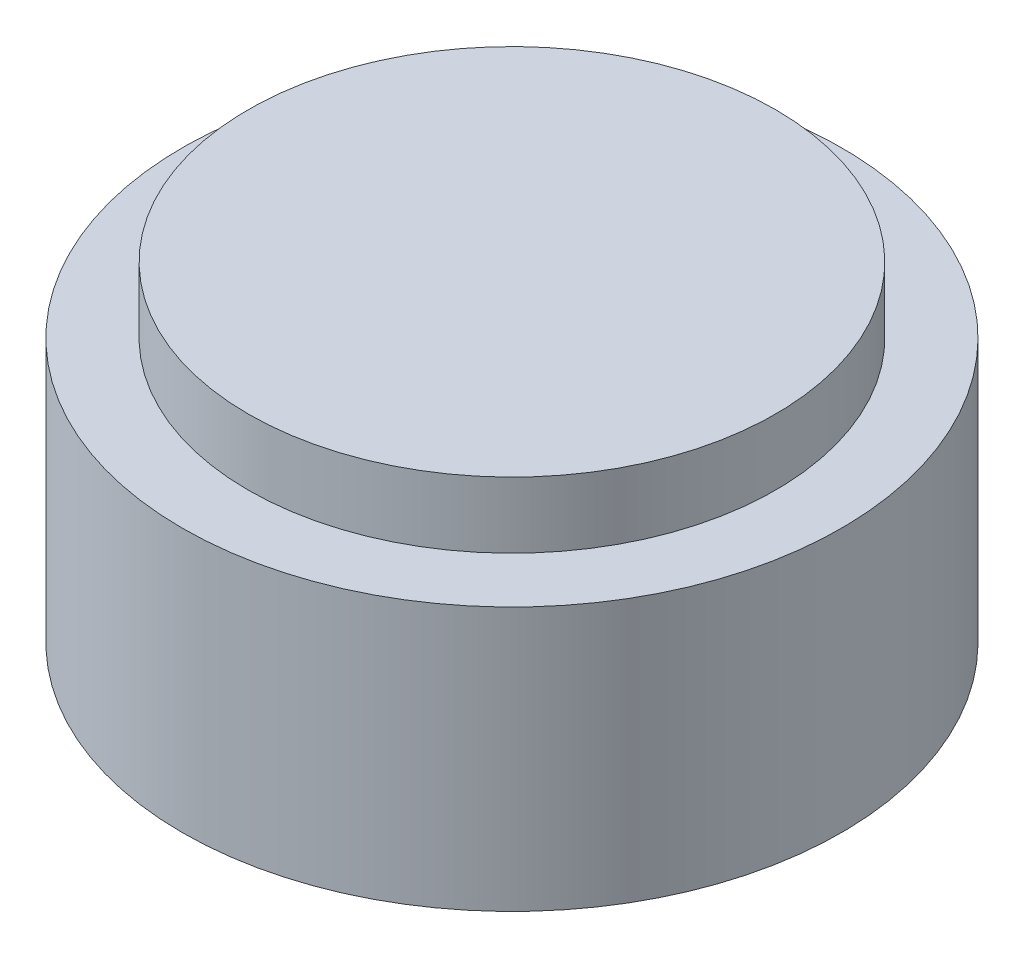
SolidWorks part; units mm, degrees
ref_plane "Front Plane" through (0, 0, 0) normal (0, 0, 1) x (1, 0, 0)
ref_plane "Top Plane" through (0, 0, 0) normal (0, 1, 0) x (1, 0, 0)
ref_plane "Right Plane" through (0, 0, 0) normal (1, 0, 0) x (0, 0, -1)
sketch "Sketch1" plane through (0, 0, 0) normal (0, 1, 0) x (1, 0, 0)
  line L0 (-0.9657, 3.0508) -> (2.8368, 1.4808)
  arc A1 (-0.9657, 3.0508) -> (2.8368, 1.4808) centre (0, 0) ccw
  circle A2 centre (0, 0) radius 15
extrude "Boss-Extrude1" add sketch "Sketch1" along normal blind 12
sketch "Sketch2" plane through (0, 12, 0) normal (0, 1, 0) x (1, 0, 0)
  circle A0 centre (0, 0) radius 12
extrude "Boss-Extrude2" add sketch "Sketch2" along normal blind 3
